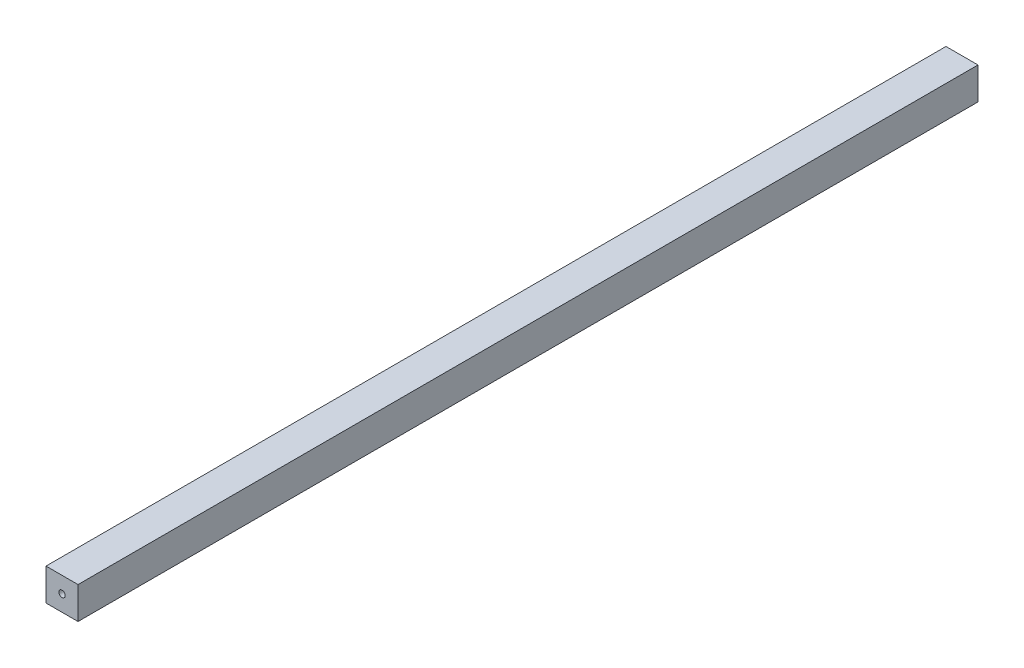
SolidWorks part; units mm, degrees
ref_plane "Płaszczyzna przednia" through (0, 0, 0) normal (0, 0, 1) x (1, 0, 0)
ref_plane "Płaszczyzna górna" through (0, 0, 0) normal (0, 1, 0) x (1, 0, 0)
ref_plane "Płaszczyzna prawa" through (0, 0, 0) normal (1, 0, 0) x (0, 0, -1)
sketch "Sketch1" plane through (0, 0, 0) normal (0, 0, 1) x (1, 0, 0)
  line L1 (0, 0) -> (20, 0)
  line L2 (0, 0) -> (0, 20)
  line L3 (0, 20) -> (20, 20)
  line L4 (20, 0) -> (20, 20)
  line L5 (0, 0) -> (20, 20) construction
  line L6 (0, 20) -> (20, 0) construction
  point P4 (10, 10)
  dimension "D1" = 20
  dimension "D2" = 20
extrude "Boss-Extrude1" add sketch "Sketch1" along normal blind 562
hole_wizard "Ø3.0mm Dowel Hole1" positions "Sketch2" profile "Sketch3" hole size "Ø3.0" standard "ANSI Metric"
sketch "Sketch2" plane through (0, 0, 0) normal (-1, 0, 0) x (0, 0, 1)
  line L0 (562, 20) -> (562, 0) construction
  line L1 (562, 0) -> (0, 0) construction
  point P0 (551, 10)
  point P10 (491, 10)
  point P11 (431, 10)
  point P12 (371, 10)
  point P13 (311, 10)
  point P14 (251, 10)
  point P15 (191, 10)
  point P16 (131, 10)
  point P17 (71, 10)
  point P18 (11, 10)
  dimension "D1" = 11
  dimension "D3" = 10
  dimension "D2" = 10
sketch "Sketch3" plane through (0, 10, 551) normal (0, 1, 0) x (0, 0, 1)
  line L0 (0, 0) -> (0, 8.9013)
  line L1 (0, 8.9013) -> (1.5, 8)
  line L2 (1.5, 8) -> (1.5, 0)
  line L5 (1.5, 0) -> (0, 0)
  line L10 (0, 8.9013) -> (-1.5, 8) construction
  line L11 (0, -6.35) -> (0, 107.95) construction
  dimension "Hole Dia." = 3
  dimension "Hole Depth" = 8
  dimension "Drill Angle" = 118
hole_wizard "Ø4.0mm Dowel Hole1" positions "Sketch4" profile "Sketch5" hole size "Ø4.0" standard "ANSI Metric"
sketch "Sketch4" plane through (0, 0, 562) normal (0, 0, 1) x (1, 0, 0)
  line L0 (0, 0) -> (20, 0) construction
  line L1 (20, 0) -> (20, 20) construction
  point P0 (10, 10)
  dimension "D1" = 10
  dimension "D2" = 10
sketch "Sketch5" plane through (10, 10, 562) normal (1, 0, 0) x (0, -1, 0)
  line L0 (0, 0) -> (0, 7.2017)
  line L1 (0, 7.2017) -> (2, 6)
  line L2 (2, 6) -> (2, 0)
  line L5 (2, 0) -> (0, 0)
  line L10 (0, 7.2017) -> (-2, 6) construction
  line L11 (0, -6.35) -> (0, 107.95) construction
  dimension "Hole Dia." = 4
  dimension "Hole Depth" = 6
  dimension "Drill Angle" = 118
hole_wizard "Ø4.0mm Dowel Hole2" positions "Sketch6" profile "Sketch7" hole size "Ø4.0" standard "ANSI Metric"
sketch "Sketch6" plane through (0, 0, 0) normal (0, 0, -1) x (-1, 0, 0)
  line L0 (-20, 0) -> (-20, 20) construction
  line L1 (0, 0) -> (-20, 0) construction
  point P0 (-10, 10)
  dimension "D1" = 10
  dimension "D2" = 10
sketch "Sketch7" plane through (10, 10, 0) normal (1, 0, 0) x (0, 1, 0)
  line L0 (0, 0) -> (0, 7.2017)
  line L1 (0, 7.2017) -> (2, 6)
  line L2 (2, 6) -> (2, 0)
  line L5 (2, 0) -> (0, 0)
  line L10 (0, 7.2017) -> (-2, 6) construction
  line L11 (0, -6.35) -> (0, 107.95) construction
  dimension "Hole Dia." = 4
  dimension "Hole Depth" = 6
  dimension "Drill Angle" = 118
